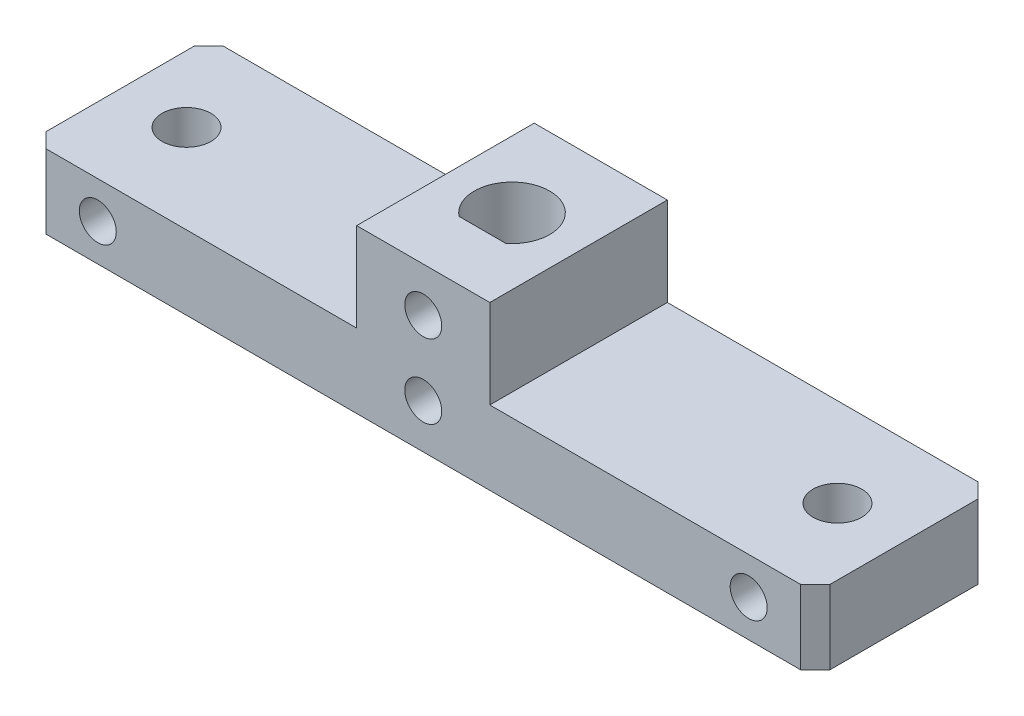
SolidWorks part; units mm, degrees
ref_plane "Top" through (0, 0, 0) normal (0, 0, 1) x (1, 0, 0)
ref_plane "Front" through (0, 0, 0) normal (0, 1, 0) x (1, 0, 0)
ref_plane "Right" through (0, 0, 0) normal (1, 0, 0) x (0, 0, -1)
sketch "Body Sketch" plane through (0, 0, 0) normal (0, 0, 1) x (1, 0, 0)
  line L0 (-26.5, 0) -> (26.5, 0)
  line L1 (26.5, 0) -> (26.5, 5)
  line L2 (26.5, 5) -> (4.5, 5)
  line L3 (4.5, 5) -> (4.5, 11)
  line L4 (4.5, 11) -> (-4.5, 11)
  line L5 (-4.5, 11) -> (-4.5, 5)
  line L6 (-4.5, 5) -> (-26.5, 5)
  line L7 (-26.5, 5) -> (-26.5, 0)
  point P8 (0, 0)
  dimension "D1" = 53
  dimension "D2" = 9
  dimension "D3" = 5
  dimension "D4" = 6
extrude "Body Extrude" add sketch "Body Sketch" against normal blind 12
sketch "Sketch2" plane through (0, 0, 0) normal (0, 1, 0) x (1, 0, 0)
  line L0 (-22.5, 6) -> (22.5, 6) construction
  line L1 (-1.5819, 4) -> (1.5819, 4)
  line L2 (0, 4) -> (0, 8.55) construction
  arc A2 (1.5819, 4) -> (-1.5819, 4) centre (0, 6) ccw
  point P8 (0, 6)
  dimension "D3" = 5.1
  dimension "D1" = 6
  dimension "D2" = 45
  dimension "D4" = 4.55
hole_wizard "Pivot M4 Holes" positions "Sketch5" profile "Sketch6" tap size "M4x0.7" standard "ANSI Metric" end condition up to next
sketch "Sketch5" plane through (0, 0, 0) normal (0, 1, 0) x (1, 0, 0)
  line L0 (-22, 6) -> (22, 6) construction
  line L2 (0, 0) -> (0, 6) construction
  point P0 (-22, 6)
  point P2 (22, 6)
  dimension "Hole Spacing" = 44
  dimension "D2" = 6
cosmetic thread "Hole Thread1" parameters "D2"=4
cosmetic thread "Hole Thread2" parameters "D2"=4
sketch "Sketch6" plane through (-22, 0, -6) normal (1, 0, 0) x (0, 0, -1)
  line L0 (0, 0) -> (0, 5)
  line L1 (0, 5) -> (1.65, 5)
  line L2 (1.65, 5) -> (1.65, 0)
  line L5 (1.65, 0) -> (0, 0)
  line L11 (0, -6.35) -> (0, 107.95) construction
  dimension "Thru Tap Drill Dia." = 3.3
  dimension "Thru Tap Drill Depth" = 5
extrude "Pivot Access Cut" cut sketch "Sketch2" along normal through all
hole_wizard "Set Screw M3 Tapped Holes" positions "Sketch7" profile "Sketch8" tap size "M3x0.5" standard "ANSI Metric"
sketch "Sketch7" plane through (0, 0, 0) normal (0, 0, 1) x (1, 0, 0)
  line L0 (-26.5, 5) -> (-26.5, 0) construction
  line L1 (-26.5, 2.5) -> (26.5, 2.5) construction
  line L2 (26.5, 0) -> (26.5, 5) construction
  line L4 (0, 0) -> (0, 11) construction
  line L5 (4.5, 11) -> (-4.5, 11) construction
  point P0 (-22, 2.5)
  point P2 (22, 2.5)
  point P4 (0, 8)
  point P6 (0, 3)
  dimension "D1" = 3
  dimension "D2" = 3
  dimension "Hole Spacing" = 44
sketch "Sketch8" plane through (-22, 2.5, 0) normal (1, 0, 0) x (0, -1, 0)
  line L0 (0, 0) -> (0, 4.35)
  line L1 (0, 4.35) -> (1.25, 4.35)
  line L2 (1.25, 4.35) -> (1.25, 0)
  line L5 (1.25, 0) -> (0, 0)
  line L11 (0, -6.35) -> (0, 107.95) construction
  dimension "Thru Tap Drill Dia." = 2.5
  dimension "Thru Tap Drill Depth" = 4.35
cosmetic thread "Hole Thread3" parameters "D2"=3
cosmetic thread "Hole Thread4" parameters "D2"=3
cosmetic thread "Hole Thread5" parameters "D2"=3
cosmetic thread "Hole Thread6" parameters "D2"=3
chamfer "Corner Chamfers" distance 1 angle 45 4 edges at (-26.5, 2.5, -12) (-26.5, 2.5, 0) (26.5, 2.5, -12) (26.5, 2.5, 0)
equation "\"Height\"= 12mm"
equation "\"D1@Body Extrude\"=\"Height\""
equation "\"D1@Sketch2\"=0.5*\"Height\""
equation "\"D2@Sketch5\"=0.5*\"Height\""
